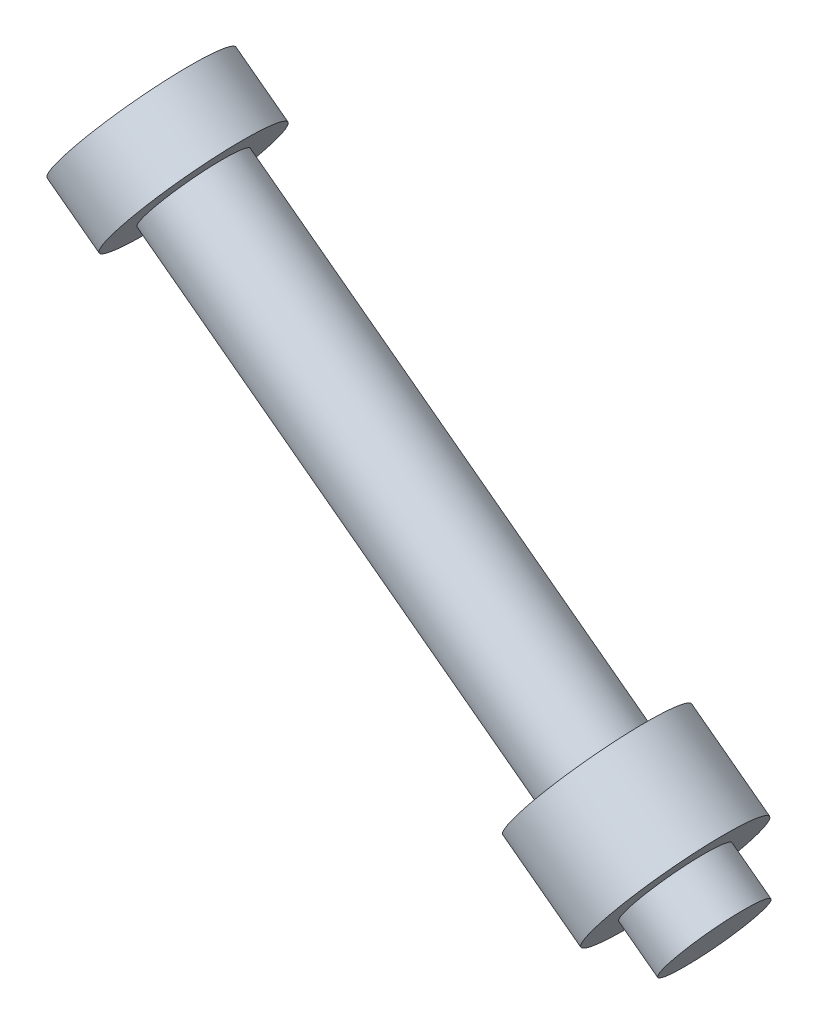
SolidWorks part; units mm, degrees
material "AISI 304"
ref_plane "Alzado" through (0, 0, 0) normal (0, 0, 1) x (1, 0, 0)
ref_plane "Planta" through (0, 0, 0) normal (0, 1, 0) x (1, 0, 0)
ref_plane "Vista lateral" through (0, 0, 0) normal (1, 0, 0) x (0, 0, -1)
sketch3d "Sk_Cabeza"
  line L0 (-234.9749, 359.1356, 0) -> (-238.1775, 361.5322, 0)
  dimension "D1" = 4
sweep "Cabeza" add path "Sk_Cabeza" circular profile diameter 10 parameters "D3"=10
sketch3d "Sk_Vastago"
  line L0 (-202.9487, 335.1706, 0) -> (-234.9749, 359.1356, 0)
  dimension "D1" = 40
sweep "Vastago" add path "Sk_Vastago" circular profile diameter 6 parameters "D3"=6
sketch3d "Sk_Tuerca"
  line L0 (-205.3507, 336.968, 0) -> (-210.1546, 340.5627, 0)
  dimension "D1" = 6
sweep "Tuerca" add path "Sk_Tuerca" circular profile diameter 10 parameters "D3"=10
